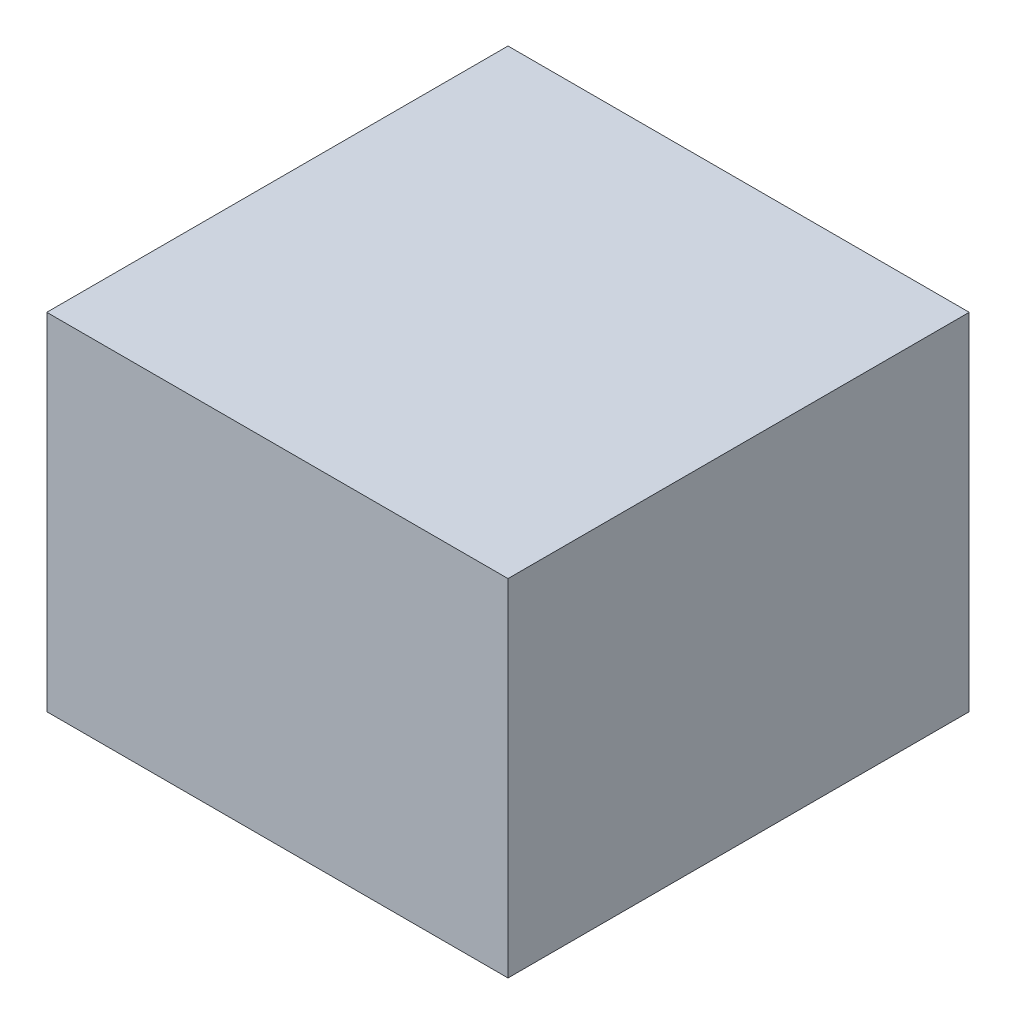
SolidWorks part; units mm, degrees
ref_plane "Front Plane" through (0, 0, 0) normal (0, 0, 1) x (1, 0, 0)
ref_plane "Top Plane" through (0, 0, 0) normal (0, 1, 0) x (1, 0, 0)
ref_plane "Right Plane" through (0, 0, 0) normal (1, 0, 0) x (0, 0, -1)
other "Configuration Table"
sketch "Sketch1" plane through (0, 0, 0) normal (0, 0, 1) x (1, 0, 0)
  line L1 (300, 320) -> (340, 320)
  line L2 (300, 320) -> (300, 350)
  line L3 (300, 350) -> (340, 350)
  line L4 (340, 320) -> (340, 350)
extrude "PACK_vakum_sensoru_1" add sketch "Sketch1" against normal blind 40 from offset 640 separate body
